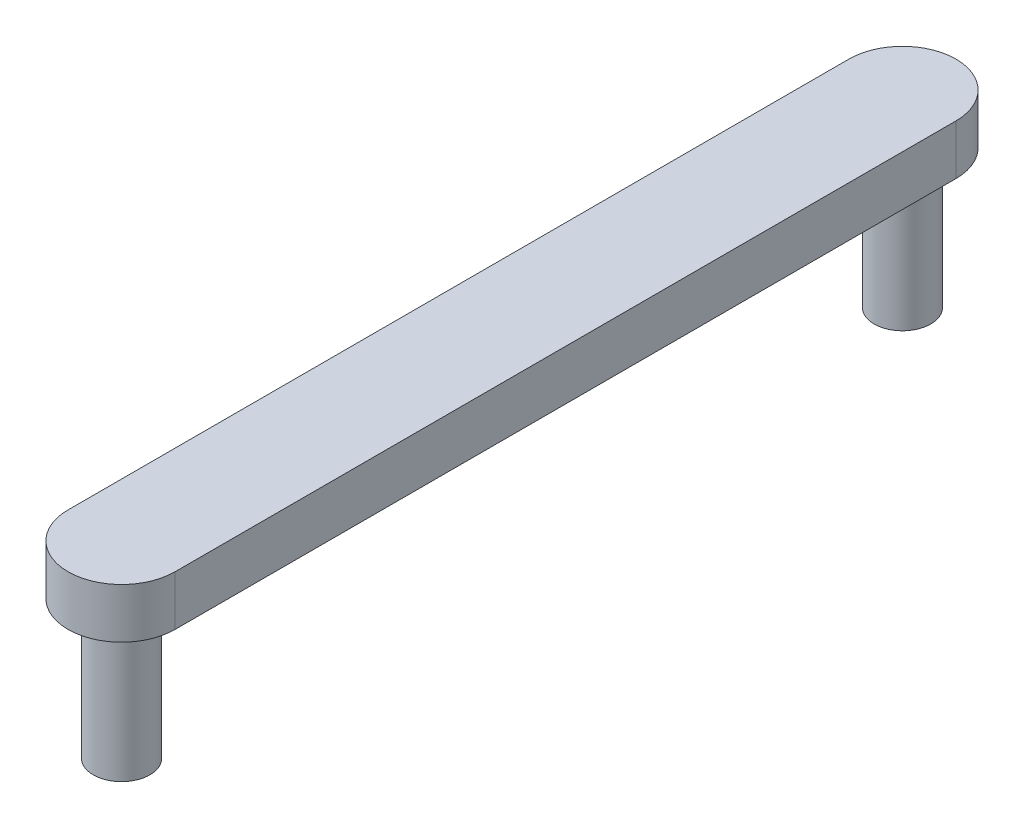
SolidWorks part; units mm, degrees
ref_plane "Front Plane" through (0, 0, 0) normal (0, 0, 1) x (1, 0, 0)
ref_plane "Top Plane" through (0, 0, 0) normal (0, 1, 0) x (1, 0, 0)
ref_plane "Right Plane" through (0, 0, 0) normal (1, 0, 0) x (0, 0, -1)
sketch "Sketch1" plane through (0, 0, 0) normal (0, 1, 0) x (1, 0, 0)
  circle A0 centre (0, 0) radius 0.9
  circle A1 centre (0, -24.8) radius 0.9
  point P5 (0, 0)
  dimension "D1" = 1.8
  dimension "D2" = 24.8
extrude "Boss-Extrude1" add sketch "Sketch1" along normal blind 4.4
sketch "Sketch2" plane through (0, 4.4, 0) normal (0, 1, 0) x (1, 0, 0)
  line L0 (0, 0) -> (0, -24.8) construction
  line L1 (1.7, 0) -> (1.7, -24.8)
  line L2 (-1.7, 0) -> (-1.7, -24.8)
  arc A0 (1.7, 0) -> (-1.7, 0) centre (0, 0) ccw
  arc A1 (-1.7, -24.8) -> (1.7, -24.8) centre (0, -24.8) ccw
  circle A2 centre (0, -24.8) radius 0.9 construction
  point P4 (0, -12.4)
  dimension "D1" = 0.8
extrude "Boss-Extrude2" add sketch "Sketch2" along normal blind 1.5875
